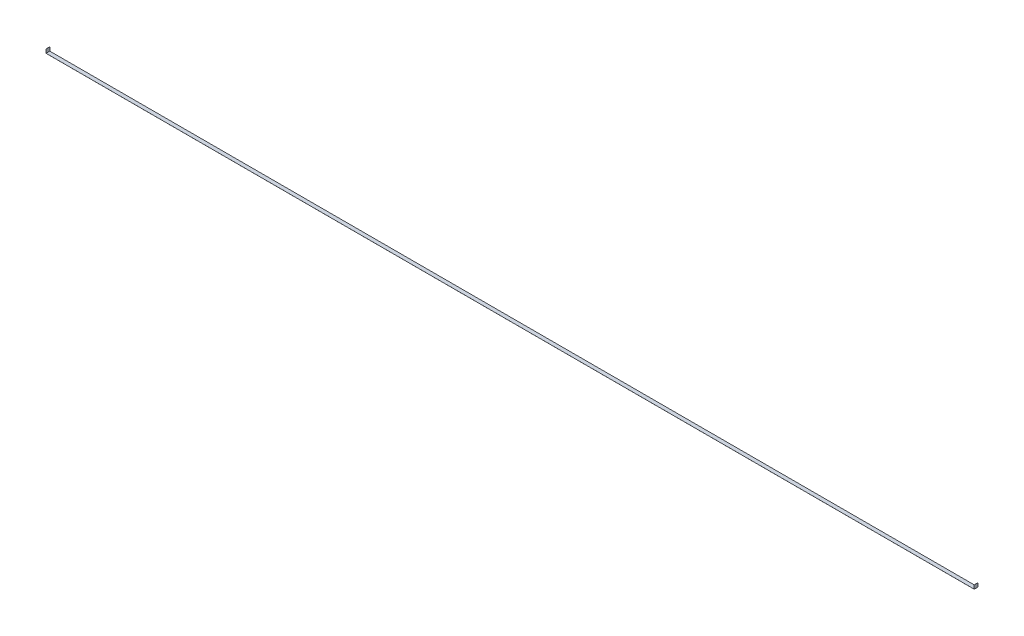
SolidWorks part; units mm, degrees
material "Nylon 101"
ref_plane "Front Plane" through (0, 0, 0) normal (0, 0, 1) x (1, 0, 0)
ref_plane "Top Plane" through (0, 0, 0) normal (0, 1, 0) x (1, 0, 0)
ref_plane "Right Plane" through (0, 0, 0) normal (1, 0, 0) x (0, 0, -1)
sketch "Sketch1" plane through (0, 0, 0) normal (0, 0, 1) x (1, 0, 0)
  line L0 (-3136.9, 0) -> (3136.9, 0)
  line L1 (3136.9, 0) -> (3136.9, 25.4)
  line L3 (-3136.9, 25.4) -> (-3136.9, 0)
  point P4 (0, 0)
  dimension "D1" = 25.4
  dimension "D2" = 6273.8
extrude "Extrude-Thin1" add sketch "Sketch1" along normal blind 25.4 thin
